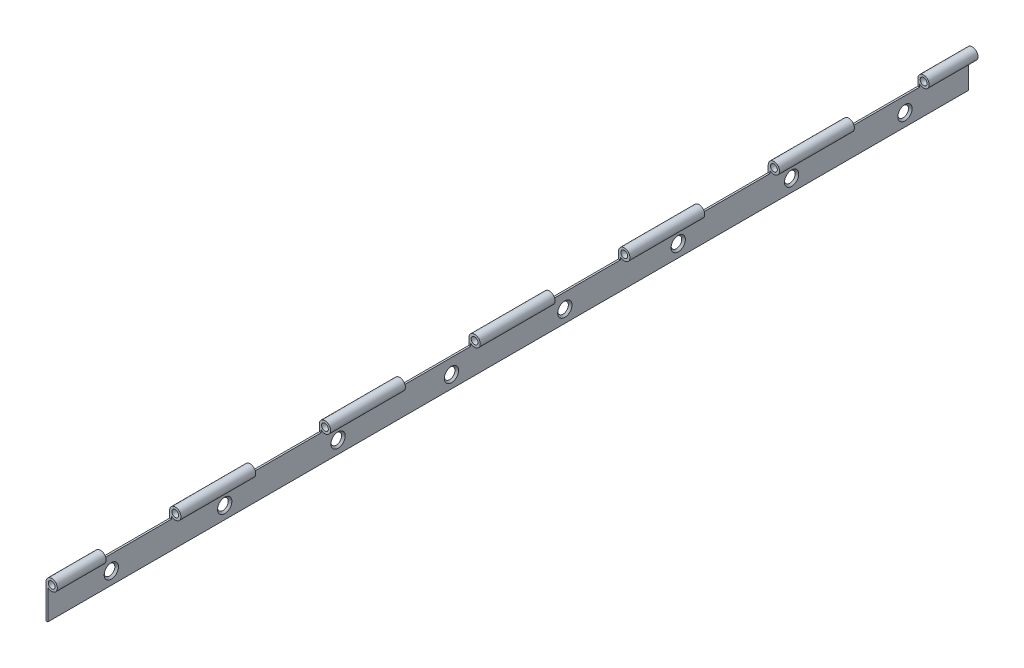
SolidWorks part; units mm, degrees
material "镀铬不锈钢"
ref_plane "前视基准面" through (0, 0, 0) normal (0, 0, 1) x (1, 0, 0)
ref_plane "上视基准面" through (0, 0, 0) normal (0, 1, 0) x (1, 0, 0)
ref_plane "右视基准面" through (0, 0, 0) normal (1, 0, 0) x (0, 0, -1)
sketch "草图1" plane through (0, 0, 0) normal (0, 0, 1) x (1, 0, 0)
  line L0 (0, 0) -> (0, 15)
  dimension "D1" = 15
extrude "拉伸-薄壁1" add sketch "草图1" along normal mid plane 406 thin
sketch "草图2" plane through (0, 0, 203) normal (0, 0, 1) x (1, 0, 0)
  circle A0 centre (2.5, 15) radius 2.5
  dimension "D1" = 5
sweep "扫描1" add profiles "草图2" path edge at (0.8, 15, 0)
sketch "草图3" plane through (0, 0, 203) normal (0, 0, 1) x (1, 0, 0)
  circle A0 centre (2.5, 15) radius 1.5
  dimension "D1" = 3
extrude "切除-拉伸1" cut sketch "草图3" against normal through all
sketch "草图10" plane through (0.8, 0, 0) normal (1, 0, 0) x (0, 0, -1)
  line L0 (-181.5, 18) -> (-148.5, 18)
  line L1 (-181.5, 12) -> (-148.5, 12)
  line L2 (-115.5, 18) -> (-82.5, 18)
  line L3 (-115.5, 12) -> (-82.5, 12)
  line L4 (-115.5, 18) -> (-115.5, 12)
  line L5 (-82.5, 18) -> (-82.5, 12)
  line L6 (-49.5, 18) -> (-16.5, 18)
  line L7 (-49.5, 12) -> (-16.5, 12)
  line L8 (-49.5, 18) -> (-49.5, 12)
  line L9 (-16.5, 18) -> (-16.5, 12)
  line L10 (-181.5, 18) -> (-181.5, 12)
  line L11 (-148.5, 18) -> (-148.5, 12)
  line L12 (16.5, 18) -> (49.5, 18)
  line L13 (16.5, 12) -> (49.5, 12)
  line L14 (16.5, 18) -> (16.5, 12)
  line L15 (49.5, 18) -> (49.5, 12)
  line L16 (82.5, 18) -> (115.5, 18)
  line L17 (82.5, 12) -> (115.5, 12)
  line L18 (82.5, 18) -> (82.5, 12)
  line L19 (115.5, 18) -> (115.5, 12)
  line L20 (148.5, 18) -> (181.5, 18)
  line L21 (148.5, 12) -> (181.5, 12)
  line L22 (148.5, 18) -> (148.5, 12)
  line L23 (181.5, 18) -> (181.5, 12)
  line L24 (214.5, 12) -> (247.5, 12) [skipped]
  line L25 (214.5, 18) -> (214.5, 12) [skipped]
  line L26 (247.5, 18) -> (247.5, 12) [skipped]
  line L30 (214.5, 18) -> (247.5, 18) [skipped]
  dimension "D1" = 33
  dimension "D2" = 21.5
  dimension "D3" = 33
  dimension "D5" = 6
extrude "切除-拉伸4" cut sketch "草图10" against normal mid plane 120
hole_wizard "M3 锥坑平头螺钉的锥形沉头孔2" positions "3D草图2" profile "草图12" countersink size "M3" standard "ISO" end condition through all
sketch3d "3D草图2"
  line L0 (0.8, 0, 203) -> (0.8, 0, -203) construction
  line L1 (0.8, 12, -175) -> (0.8, 0, -175) construction
  line L3 (0.8, 0, -203) -> (0.8, 13.167, -203) construction
  point P0 (0.8, 5.5, -175)
  dimension "D1" = 5.5
  dimension "D2" = 28
sketch "草图12" plane through (0.8, 5.5, -175) normal (0, 1, 0) x (0, 0, -1)
  line L0 (0, 0) -> (0, 0.8)
  line L1 (0, 0.8) -> (1.7, 0.8)
  line L2 (1.7, 0.8) -> (1.7, 1.45)
  line L3 (1.7, 1.45) -> (3.15, 0)
  line L5 (3.15, 0) -> (0, 0)
  line L6 (-1.7, 1.45) -> (-3.15, 0) construction
  line L11 (0, -6.35) -> (0, 107.95) construction
  dimension "Í¨¿×¿×Ö±¾¶" = 3.4
  dimension "Í¨¿×¿×Éî¶È" = 0.8
  dimension "½ü¶Ë×¶ÐÎ³ÁÍ·¿×Ö±¾¶" = 6.3
  dimension "½ü¶Ë×¶ÐÎ³ÁÍ·¿×½Ç¶È" = 90
pattern_linear "阵列(线性)1" count 8 spacing 50 along (0, 0, 1) of "M3 锥坑平头螺钉的锥形沉头孔2"
